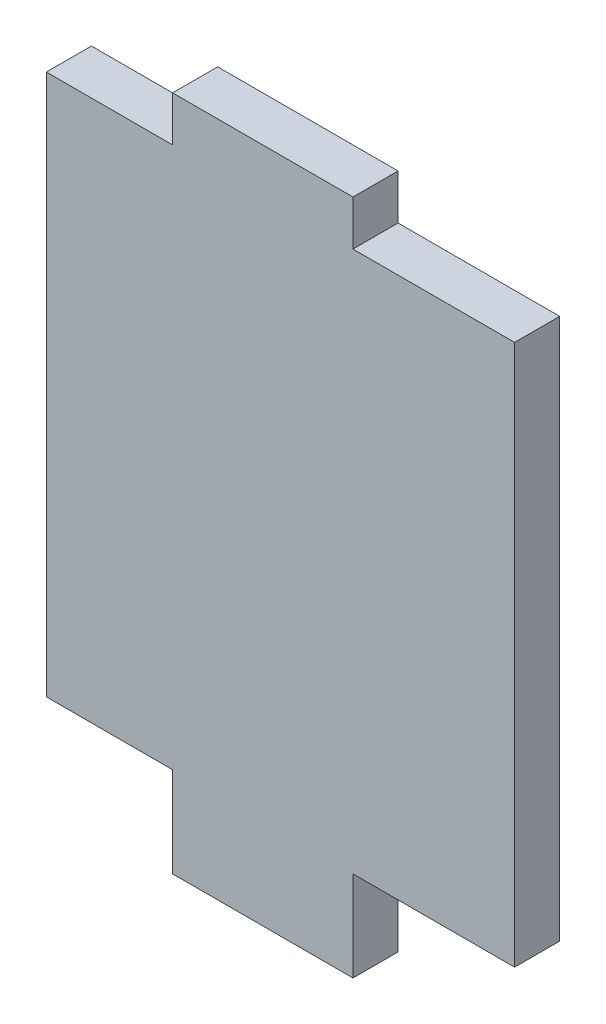
SolidWorks part; units mm, degrees
material "Beech"
ref_plane "Front" through (0, 0, 0) normal (0, 0, 1) x (1, 0, 0)
ref_plane "Top" through (0, 0, 0) normal (0, 1, 0) x (1, 0, 0)
ref_plane "Right" through (0, 0, 0) normal (1, 0, 0) x (0, 0, -1)
sketch "Sketch1" plane through (0, 0, 0) normal (0, 0, 1) x (1, 0, 0)
  line L0 (-12.9808, 16.25) -> (-5.9808, 16.25)
  line L1 (-12.9808, -18.75) -> (12.9808, -18.75) construction
  line L2 (-12.9808, -18.75) -> (-12.9808, 18.75) construction
  line L3 (-12.9808, 18.75) -> (12.9808, 18.75) construction
  line L4 (12.9808, -18.75) -> (12.9808, 18.75) construction
  line L5 (-12.9808, -18.75) -> (12.9808, 18.75) construction
  line L6 (-12.9808, 18.75) -> (12.9808, -18.75) construction
  line L7 (-5.9808, 16.25) -> (-5.9808, 18.75)
  line L8 (-5.9808, 18.75) -> (4.0192, 18.75)
  line L9 (4.0192, 18.75) -> (4.0192, 16.25)
  line L10 (4.0192, 16.25) -> (12.9808, 16.25)
  line L11 (12.9808, 16.25) -> (12.9808, -13.75)
  line L12 (12.9808, -13.75) -> (4.0192, -13.75)
  line L13 (4.0192, -13.75) -> (4.0192, -18.75)
  line L14 (4.0192, -18.75) -> (-5.9808, -18.75)
  line L15 (-5.9808, -18.75) -> (-5.9808, -13.75)
  line L16 (-5.9808, -13.75) -> (-12.9808, -13.75)
  line L17 (-12.9808, -13.75) -> (-12.9808, 16.25)
  point P0 (0, 0)
  dimension "D1" = 25.9615
  dimension "D2" = 37.5
  dimension "D3" = 5
  dimension "D4" = 2.5
  dimension "D5" = 7
  dimension "D6" = 10
extrude "Boss-Extrude1" add sketch "Sketch1" along normal blind 2.5
